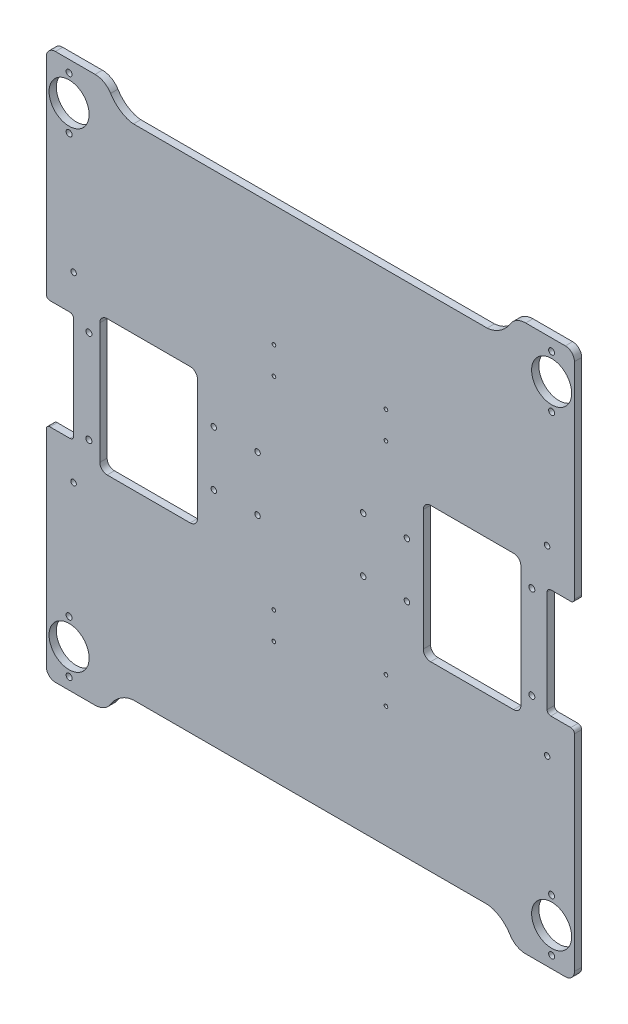
SolidWorks part; units mm, degrees
ref_plane "Front Plane" through (0, 0, 0) normal (0, 0, 1) x (1, 0, 0)
ref_plane "Top Plane" through (0, 0, 0) normal (0, 1, 0) x (1, 0, 0)
ref_plane "Right Plane" through (0, 0, 0) normal (1, 0, 0) x (0, 0, -1)
ref_plane "Plane1" through (0, 150, 0) normal (0, 1, 0) x (1, 0, 0)
ref_plane "Plane2" through (0, -150, 0) normal (0, 1, 0) x (1, 0, 0)
ref_plane "Plane3" through (150, 0, 0) normal (1, 0, 0) x (0, 0, -1)
ref_plane "Plane4" through (-150, 0, 0) normal (1, 0, 0) x (0, 0, -1)
sketch "Sketch2" plane through (0, 0, 0) normal (0, 0, 1) x (1, 0, 0)
  line L0 (0, -10.2) -> (0, 50.0764) construction
  line L5 (-53, 40) -> (-53, 10) construction
  line L23 (-140, 175) -> (-118.2051, 175)
  line L24 (139.6652, 116) -> (168.3348, 116) construction
  line L40 (-152.1866, -81.0661) -> (-123.5266, -81.0661) construction
  line L47 (-66, 62.1714) -> (-111.5977, 62.1714)
  line L48 (66, 62.1714) -> (111.5977, 62.1714)
  line L49 (62, 58.1714) -> (62, -8.1714)
  line L50 (66, -12.1714) -> (111.5977, -12.1714)
  line L51 (115.5977, 58.1714) -> (115.5977, -8.1714)
  line L52 (62, 62.1714) -> (115.5977, -12.1714) construction
  line L53 (62, -12.1714) -> (115.5977, 62.1714) construction
  line L54 (-62, 58.1714) -> (-62, -8.1714)
  line L55 (-66, -12.1714) -> (-111.5977, -12.1714)
  line L56 (-115.5977, 58.1714) -> (-115.5977, -8.1714)
  line L57 (177.1787, -66.0847) -> (177.1787, 11.9153) construction
  line L66 (94.5, 117.9861) -> (-94.5, 117.9861) construction
  line L70 (-121.5977, 50.5) -> (-121.5977, -0.5) construction
  line L73 (-145, 170) -> (-145, 57)
  line L74 (162.5, 25) -> (139.6652, 25) construction
  line L79 (-145, -7) -> (-145, -120)
  line L80 (-143, -5) -> (-132, -5)
  line L82 (-143, 55) -> (-132, 55)
  line L83 (-130, -3) -> (-130, 53)
  line L84 (-145.4163, 25) -> (-130, 55) construction
  line L85 (-145.4163, 25) -> (-130, -5) construction
  line L88 (145.4163, 25) -> (130, -5) construction
  line L89 (145.4163, 25) -> (130, 55) construction
  line L90 (121.5977, 50.5) -> (121.5977, -0.5) construction
  line L91 (130, -3) -> (130, 53)
  line L92 (143, 55) -> (132, 55)
  line L93 (143, -5) -> (132, -5)
  line L94 (145, -7) -> (145, -120)
  line L95 (145, 170) -> (145, 57)
  line L97 (140, -125) -> (118.2051, -125)
  line L99 (-97.0952, 162) -> (97.0952, 162)
  line L100 (118.2051, 175) -> (140, 175)
  line L101 (-97.0952, -112) -> (97.0952, -112)
  line L102 (-118.2051, -125) -> (-140, -125)
  circle A1 centre (-132.4733, 168.5604) radius 1.65
  circle A2 centre (-132.4733, 139.8908) radius 1.65
  circle A3 centre (132.4733, 168.5604) radius 1.65
  circle A4 centre (132.4733, 139.8908) radius 1.65
  circle A9 centre (132.4733, 154.2256) radius 11
  circle A10 centre (-132.4733, 154.2256) radius 11
  circle A17 centre (121.5977, -0.5) radius 1.65
  circle A18 centre (121.5977, 50.5) radius 1.65
  circle A19 centre (-121.5977, -0.5) radius 1.65
  circle A20 centre (-121.5977, 50.5) radius 1.65
  circle A27 centre (-29, 10) radius 1.5
  circle A32 centre (-29, 40) radius 1.5
  circle A33 centre (-53, 40) radius 1.5
  circle A34 centre (-53, 10) radius 1.5
  circle A35 centre (53, 10) radius 1.5
  circle A36 centre (29, 10) radius 1.5
  circle A37 centre (29, 40) radius 1.5
  circle A38 centre (53, 40) radius 1.5
  arc A48 (62, -8.1714) -> (66, -12.1714) centre (66, -8.1714) ccw
  arc A49 (111.5977, -12.1714) -> (115.5977, -8.1714) centre (111.5977, -8.1714) ccw
  arc A50 (111.5977, 62.1714) -> (115.5977, 58.1714) centre (111.5977, 58.1714) cw
  arc A51 (66, 62.1714) -> (62, 58.1714) centre (66, 58.1714) ccw
  arc A52 (-111.5977, 62.1714) -> (-115.5977, 58.1714) centre (-111.5977, 58.1714) ccw
  arc A53 (-66, 62.1714) -> (-62, 58.1714) centre (-66, 58.1714) cw
  arc A54 (-62, -8.1714) -> (-66, -12.1714) centre (-66, -8.1714) cw
  arc A55 (-111.5977, -12.1714) -> (-115.5977, -8.1714) centre (-111.5977, -8.1714) cw
  circle A68 centre (132.4733, -118.5604) radius 1.65
  circle A69 centre (132.4733, -89.8908) radius 1.65
  circle A70 centre (132.4733, -104.2256) radius 11
  circle A71 centre (-132.4733, -104.2256) radius 11
  circle A72 centre (-132.4733, -89.8908) radius 1.65
  circle A73 centre (-132.4733, -118.5604) radius 1.65
  arc A84 (-140, 175) -> (-145, 170) centre (-140, 170) ccw
  arc A85 (140, 175) -> (145, 170) centre (140, 170) cw
  arc A86 (140, -125) -> (145, -120) centre (140, -120) ccw
  arc A87 (-140, -125) -> (-145, -120) centre (-140, -120) cw
  circle A89 centre (130, 75) radius 1.5
  arc A90 (109.6762, 170.221) -> (118.2051, 175) centre (118.2051, 165) cw
  arc A91 (-109.6762, 170.221) -> (-118.2051, 175) centre (-118.2051, 165) ccw
  arc A92 (109.6762, -120.221) -> (118.2051, -125) centre (118.2051, -115) ccw
  circle A93 centre (41.5, 95.575) radius 1
  circle A94 centre (41.5, 80.575) radius 1
  circle A95 centre (-20, 80.575) radius 1
  circle A96 centre (-20, 95.575) radius 1
  arc A97 (-109.6762, -120.221) -> (-118.2051, -125) centre (-118.2051, -115) cw
  circle A98 centre (-20, -45.575) radius 1
  circle A99 centre (-20, -30.575) radius 1
  circle A100 centre (41.5, -30.575) radius 1
  circle A101 centre (41.5, -45.575) radius 1
  circle A102 centre (130, -25) radius 1.5
  circle A103 centre (-130, 75) radius 1.5
  circle A104 centre (-130, -25) radius 1.5
  arc A105 (-143, -5) -> (-145, -7) centre (-143, -7) ccw
  arc A106 (-132, -5) -> (-130, -3) centre (-132, -3) ccw
  arc A107 (-143, 55) -> (-145, 57) centre (-143, 57) cw
  arc A108 (-132, 55) -> (-130, 53) centre (-132, 53) cw
  arc A109 (143, -5) -> (145, -7) centre (143, -7) cw
  arc A110 (132, -5) -> (130, -3) centre (132, -3) cw
  arc A111 (143, 55) -> (145, 57) centre (143, 57) ccw
  arc A112 (132, 55) -> (130, 53) centre (132, 53) ccw
  spline S0 degree 3 poles (-109.6762, 170.221) (-107.0761, 165.9736) (-102.1422, 162.2953) (-97.0952, 162) knots 0.251036 0.251036 0.251036 0.251036 1 1 1 1
  spline S1 degree 3 poles (109.6762, 170.221) (107.0761, 165.9736) (102.1422, 162.2953) (97.0952, 162) knots 0.251036 0.251036 0.251036 0.251036 1 1 1 1
  spline S2 degree 3 poles (109.6762, -120.221) (107.0761, -115.9736) (102.1422, -112.2953) (97.0952, -112) knots 0.251036 0.251036 0.251036 0.251036 1 1 1 1
  spline S3 degree 3 poles (-109.6762, -120.221) (-107.0761, -115.9736) (-102.1422, -112.2953) (-97.0952, -112) knots 0.251036 0.251036 0.251036 0.251036 1 1 1 1
  point P0 (0, 0)
  point P2 (0, 0)
  point P4 (0, 150)
  point P7 (-145.4163, 25)
  point P11 (-121.5977, 25)
  point P12 (88.7989, 25)
  point P15 (-145, 175)
  point P23 (-53, 25)
  point P24 (0, -20)
  point P32 (145, 175)
  point P33 (-130, 25)
  point P46 (145, -125)
  point P82 (177.1787, -27.0847)
  point P108 (-145, -125)
  point P111 (-115.5977, 25)
  point P112 (145.4163, 25)
  point P122 (0, 75)
  point P132 (-62, 25)
  point P145 (0, 162)
  point P167 (-145, -5)
  point P173 (-145, 55)
  point P183 (0, -25)
  point P189 (145, -5)
  point P195 (145, 55)
  point P199 (0, 0)
  point P200 (0, 0)
  point P201 (0, 0)
  point P202 (0, 0)
  point P203 (0, 0)
  point P204 (0, 0)
  point P205 (-130, 75)
  point P206 (130, 75)
  point P207 (130, -25)
  point P208 (-130, -25)
  dimension "D3" = 51
  dimension "D7" = 145
  dimension "D8" = 3.3
  dimension "D9" = 5
  dimension "D10" = 22
  dimension "D11" = 74.3428
  dimension "D12" = 13
  dimension "D13" = 53.5977
  dimension "D16" = 62
  dimension "D17" = 15
  dimension "D18" = 60
  dimension "D19" = 3.3
  dimension "D6" = 14.3348
  dimension "D20" = 14.3348
  dimension "D21" = 150
  dimension "D23" = 3
  dimension "D24" = 3
  dimension "D25" = 3
  dimension "D26" = 3
  dimension "D29" = 24
  dimension "D31" = 4
  dimension "D32" = 3
  dimension "D33" = 3
  dimension "D34" = 2
  dimension "D35" = 37.1714
  dimension "D36" = 3
  dimension "D4" = 3.3
  dimension "D5" = 6
  dimension "D22" = 15
  dimension "D28" = 24
  dimension "D30" = 29
  dimension "D15" = 3
  dimension "D14" = 10
extrude "Boss-Extrude1" add sketch "Sketch2" along normal blind 4
